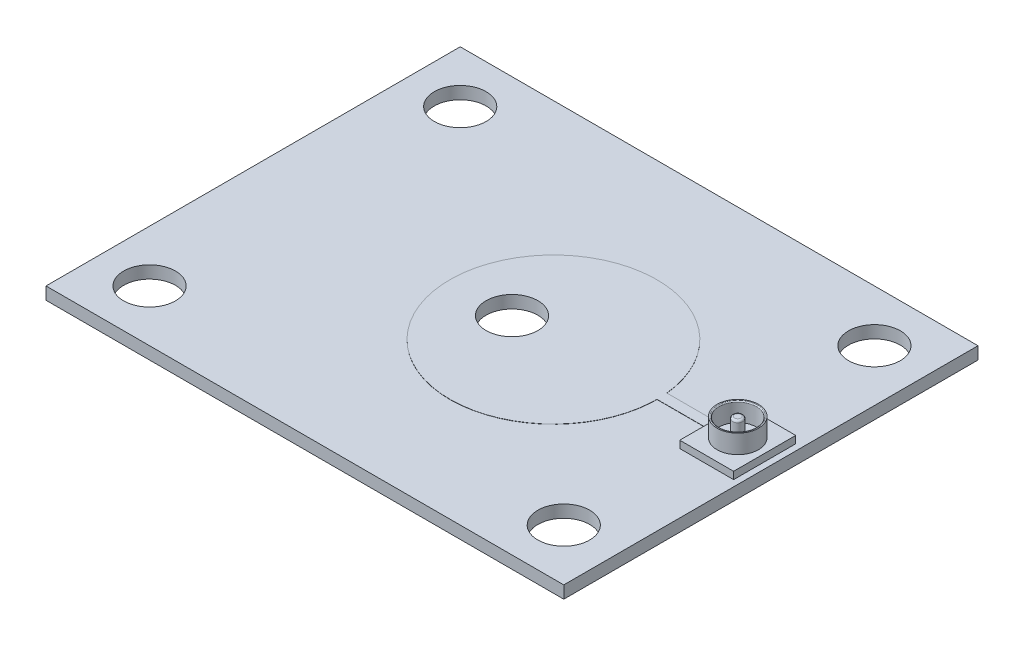
SolidWorks part; units mm, degrees
ref_plane "Front Plane" through (0, 0, 0) normal (0, 0, 1) x (1, 0, 0)
ref_plane "Top Plane" through (0, 0, 0) normal (0, 1, 0) x (1, 0, 0)
ref_plane "Right Plane" through (0, 0, 0) normal (1, 0, 0) x (0, 0, -1)
sketch "Sketch1" plane through (0, 0, 0) normal (0, 1, 0) x (1, 0, 0)
  line L1 (-12.5, -10) -> (12.5, -10)
  line L2 (-12.5, -10) -> (-12.5, 10)
  line L3 (-12.5, 10) -> (12.5, 10)
  line L4 (12.5, -10) -> (12.5, 10)
  line L5 (-12.5, -10) -> (12.5, 10) construction
  line L6 (-12.5, 10) -> (12.5, -10) construction
  point P0 (0, 0)
  dimension "D1" = 25
  dimension "D2" = 20
extrude "Boss-Extrude1" add sketch "Sketch1" along normal blind 0.6
sketch "Sketch2" plane through (0, 0.6, 0) normal (0, 1, 0) x (1, 0, 0)
  line L0 (-12.5, 10) -> (-12.5, -10) construction
  line L1 (12.5, 10) -> (-12.5, 10) construction
  line L2 (0, 10) -> (0, -10) construction
  line L3 (-12.5, -10) -> (12.5, -10) construction
  line L4 (-12.5, 0) -> (12.5, 0) construction
  line L5 (12.5, -10) -> (12.5, 10) construction
  circle A0 centre (-10, 7.5) radius 1.25
  circle A2 centre (10, 7.5) radius 1.25
  circle A3 centre (10, -7.5) radius 1.25
  circle A4 centre (-10, -7.5) radius 1.25
  circle A6 centre (0, 0) radius 1.25
  dimension "D1" = 2.5
  dimension "D2" = 2.5
  dimension "D3" = 2.5
  dimension "D4" = 2.5
extrude "Cut-Extrude1" cut sketch "Sketch2" against normal blind 0.6
sketch "Sketch4" plane through (0, 0.6, 0) normal (0, 1, 0) x (1, 0, 0)
  line L0 (-12.5, 0) -> (12.5, 0) construction
  line L1 (-12.5, 10) -> (-12.5, -10) construction
  line L2 (12.5, -10) -> (12.5, 10) construction
  line L4 (12.2, -1.5) -> (9.6, -1.5)
  line L5 (12.2, -1.5) -> (12.2, 1.5)
  line L6 (12.2, 1.5) -> (9.6, 1.5)
  line L7 (9.6, -1.5) -> (9.6, 1.5)
  line L8 (12.2, -1.5) -> (9.6, 1.5) construction
  line L9 (12.2, 1.5) -> (9.6, -1.5) construction
  point P6 (10.9, 0)
  dimension "D1" = 2.6
  dimension "D2" = 3
  dimension "D3" = 0.3
extrude "Boss-Extrude2" add sketch "Sketch4" along normal blind 0.35
sketch "Sketch5" plane through (0, 0.95, 0) normal (0, 1, 0) x (1, 0, 0)
  line L0 (10.9, 1.5) -> (10.9, -1.5) construction
  line L1 (12.2, 1.5) -> (9.6, 1.5) construction
  line L2 (9.6, -1.5) -> (12.2, -1.5) construction
  circle A0 centre (10.9, 0) radius 1
  dimension "D1" = 2
extrude "Boss-Extrude3" add sketch "Sketch5" along normal blind 0.9
sketch "Sketch6" plane through (0, 1.85, 0) normal (0, 1, 0) x (1, 0, 0)
  circle A0 centre (10.9, 0) radius 0.25
  circle A1 centre (10.9, 0) radius 0.9
  dimension "D1" = 0.5
  dimension "D2" = 1.8
extrude "Cut-Extrude2" cut sketch "Sketch6" against normal blind 0.9
fillet "Fillet1" radius 0.1 1 edges at (10.9, 1.85, 0.25)
fillet "Fillet2" radius 0.05 1 edges at (10.9, 1.85, 0.9)
sketch "Sketch8" plane through (0, 0.6, 0) normal (0, 1, 0) x (1, 0, 0)
  line L0 (0, 0) -> (2, 0) construction
  line L2 (7, 0) -> (6.991, -0.2999)
  line L5 (9.6, 0) -> (1.25, 0)
  line L6 (9.6, 1.5) -> (9.6, -1.5) construction
  line L7 (9.6, 0) -> (9.6, 0.5)
  line L8 (9.6, 0.5) -> (1.25, 0.5)
  line L11 (1.25, 0.5) -> (1.25, 0)
  circle A0 centre (2, 0) radius 5
  circle A1 centre (0, 0) radius 1.25 construction
  circle M13 centre (0, 0) radius 1.25
  line M17 (9.6, -1.5) -> (9.6, 1.5)
  dimension "D2" = 10
  dimension "D1" = 2
  dimension "D3" = 0.3
  dimension "D4" = 0.5
extrude "Boss-Extrude9" add sketch "Sketch8" along normal blind 0.01 contours L8 A0 L2 L5 L11 M13 | L5 A0 L8 L11 | A0 L5 L8 M17
